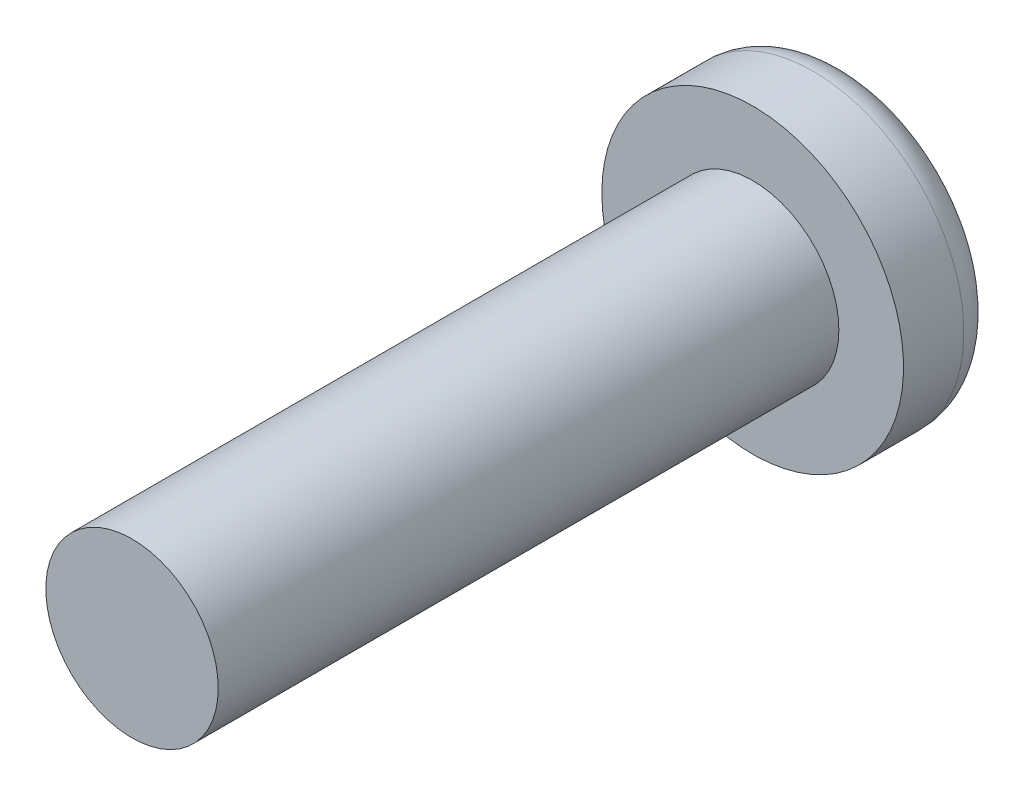
SolidWorks part; units mm, degrees
ref_plane "前视基准面" through (0, 0, 0) normal (0, 0, 1) x (1, 0, 0)
ref_plane "上视基准面" through (0, 0, 0) normal (0, 1, 0) x (1, 0, 0)
ref_plane "右视基准面" through (0, 0, 0) normal (1, 0, 0) x (0, 0, -1)
sketch "草图1" plane through (0, 0, 0) normal (0, 0, 1) x (1, 0, 0)
  circle A0 centre (0, 0) radius 5
  dimension "D1" = 10
extrude "凸台-拉伸1" add sketch "草图1" along normal blind 36
sketch "草图2" plane through (0, 0, 0) normal (0, 0, -1) x (-1, 0, 0)
  circle A0 centre (0, 0) radius 8.75
  dimension "D1" = 17.5
extrude "凸台-拉伸2" add sketch "草图2" along normal blind 5.5
fillet "圆角1" radius 2 1 edges at (-8.75, 0, -5.5)
sketch "草图3" plane through (0, 0, -5.5) normal (0, 0, -1) x (-1, 0, 0)
  line L0 (-0.7071, 0.7071) -> (-0.7071, 6.0064)
  line L1 (1, -1) -> (-1, -1) construction
  line L2 (1, -1) -> (1, 1) construction
  line L3 (1, 1) -> (-1, 1) construction
  line L4 (-1, -1) -> (-1, 1) construction
  line L5 (1, -1) -> (-1, 1) construction
  line L6 (1, 1) -> (-1, -1) construction
  line L7 (0.7071, 0.7071) -> (0.7071, 6.0064)
  line L8 (0.7071, 6.0064) -> (-0.7071, 6.0064)
  line L9 (0.7071, 0.7071) -> (6.0064, 0.7071)
  line L10 (0.7071, -0.7071) -> (6.0064, -0.7071)
  line L11 (6.0064, -0.7071) -> (6.0064, 0.7071)
  line L12 (0.7071, -0.7071) -> (0.7071, -6.0064)
  line L13 (-0.7071, -0.7071) -> (-0.7071, -6.0064)
  line L14 (-0.7071, -6.0064) -> (0.7071, -6.0064)
  line L15 (-0.7071, -0.7071) -> (-6.0064, -0.7071)
  line L16 (-0.7071, 0.7071) -> (-6.0064, 0.7071)
  line L17 (-6.0064, 0.7071) -> (-6.0064, -0.7071)
  circle A0 centre (0, 0) radius 1 construction
  dimension "D1" = 4
extrude "切除-拉伸1" cut sketch "草图3" against normal blind 2
